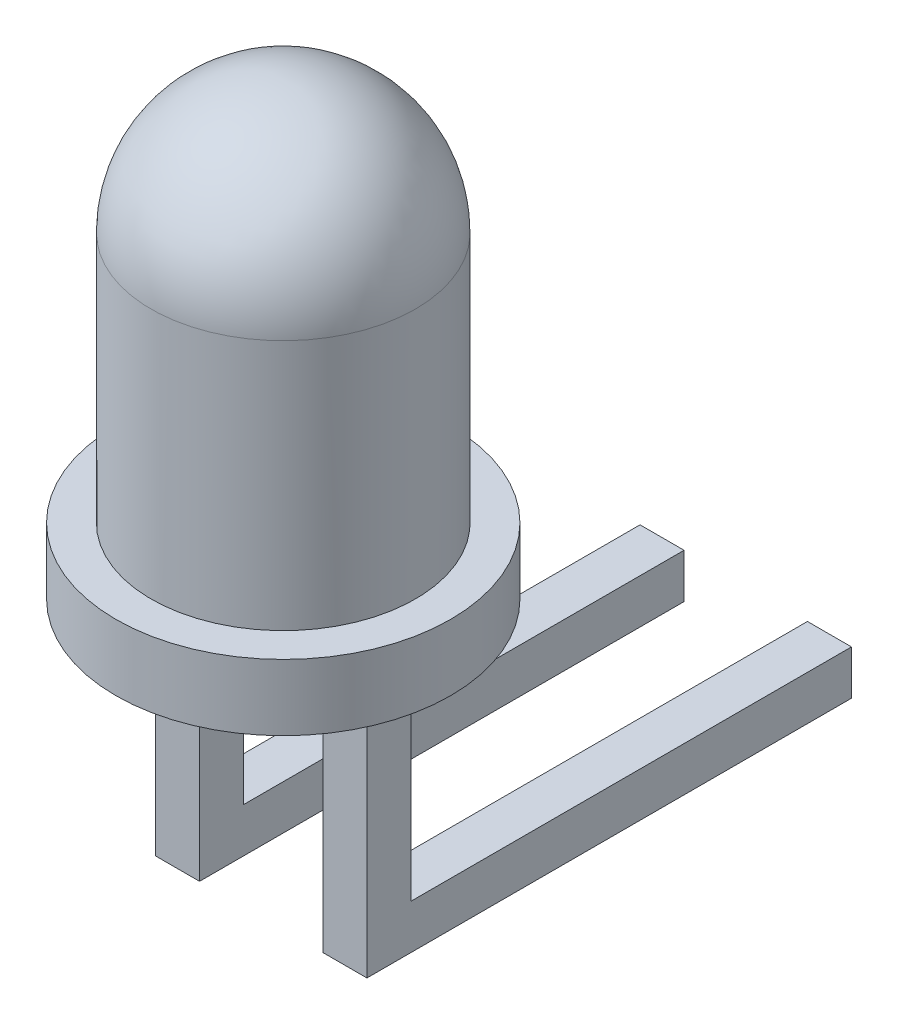
SolidWorks part; units mm, degrees
ref_plane "Přední rovina" through (0, 0, 0) normal (0, 0, 1) x (1, 0, 0)
ref_plane "Horní rovina" through (0, 0, 0) normal (0, 1, 0) x (1, 0, 0)
ref_plane "Pravá rovina" through (0, 0, 0) normal (1, 0, 0) x (0, 0, -1)
sketch "Skica1" plane through (0, 0, 0) normal (0, 0, 1) x (1, 0, 0)
  line L0 (-1.5, 6.0665) -> (-1.5, 3.2165)
  line L1 (-1.9, 2.4665) -> (0, 2.4665)
  line L2 (0, 7.5665) -> (0, 2.4665)
  line L3 (-1.5, 3.2165) -> (-1.9, 3.2165)
  line L4 (-1.9, 3.2165) -> (-1.9, 2.4665)
  line L5 (0, 7.5665) -> (0, 2.4665) construction
  line L6 (0, 7.5665) -> (0, 8.2497) construction
  arc A0 (0, 7.5665) -> (-1.5, 6.0665) centre (0, 6.0665) ccw
  dimension "D1" = 5.1
  dimension "D2" = 3
  dimension "D3" = 3.8
revolve "Rotovat1" add sketch "Skica1" angle 360 about L5
sketch "Skica2" plane through (0, 0, 0) normal (0, 0, 1) x (1, 0, 0)
  line L0 (0.7, 2.4665) -> (1.2, 2.4665)
  line L1 (-1.9, 2.4665) -> (1.9, 2.4665) construction
  line L2 (1.2, 2.4665) -> (1.2, -0.5335)
  line L3 (-0.7, -0.5335) -> (-1.2, -0.5335)
  line L4 (1.2, -0.5335) -> (0.7, -0.5335)
  line L6 (0.7, -0.5335) -> (0.7, 2.4665)
  line L7 (-0.7, 2.4665) -> (-0.7, -0.5335)
  line L11 (-1.2, -0.5335) -> (-1.2, 2.4665)
  line L12 (-0.7, 2.4665) -> (-1.2, 2.4665)
  dimension "D1" = 0.5
  dimension "D2" = 3
  dimension "D3" = 0.7
  dimension "D4" = 0.7
  dimension "D5" = 0.5
extrude "Přidat vysunutím1" add sketch "Skica2" along normal mid plane 0.5
sketch "Skica3" plane through (0, 0, -0.25) normal (0, 0, -1) x (-1, 0, 0)
  line L0 (0.7, -0.5335) -> (0.7, 2.4665) construction
  line L1 (1.2, -0.5335) -> (0.7, -0.5335)
  line L2 (1.2, -0.5335) -> (1.2, -0.0287)
  line L3 (1.2, -0.0287) -> (0.7, -0.0287)
  line L4 (0.7, -0.5335) -> (0.7, -0.0287)
  line L5 (-1.2, -0.5335) -> (-1.2, 2.4665) construction
  line L6 (-0.7, -0.5335) -> (-1.2, -0.5335)
  line L7 (-0.7, -0.5335) -> (-0.7, -0.0287)
  line L8 (-0.7, -0.0287) -> (-1.2, -0.0287)
  line L9 (-1.2, -0.5335) -> (-1.2, -0.0287)
  dimension "D1" = 0.5048
  dimension "D2" = 0.5048
extrude "Přidat vysunutím2" add sketch "Skica3" along normal blind 5
